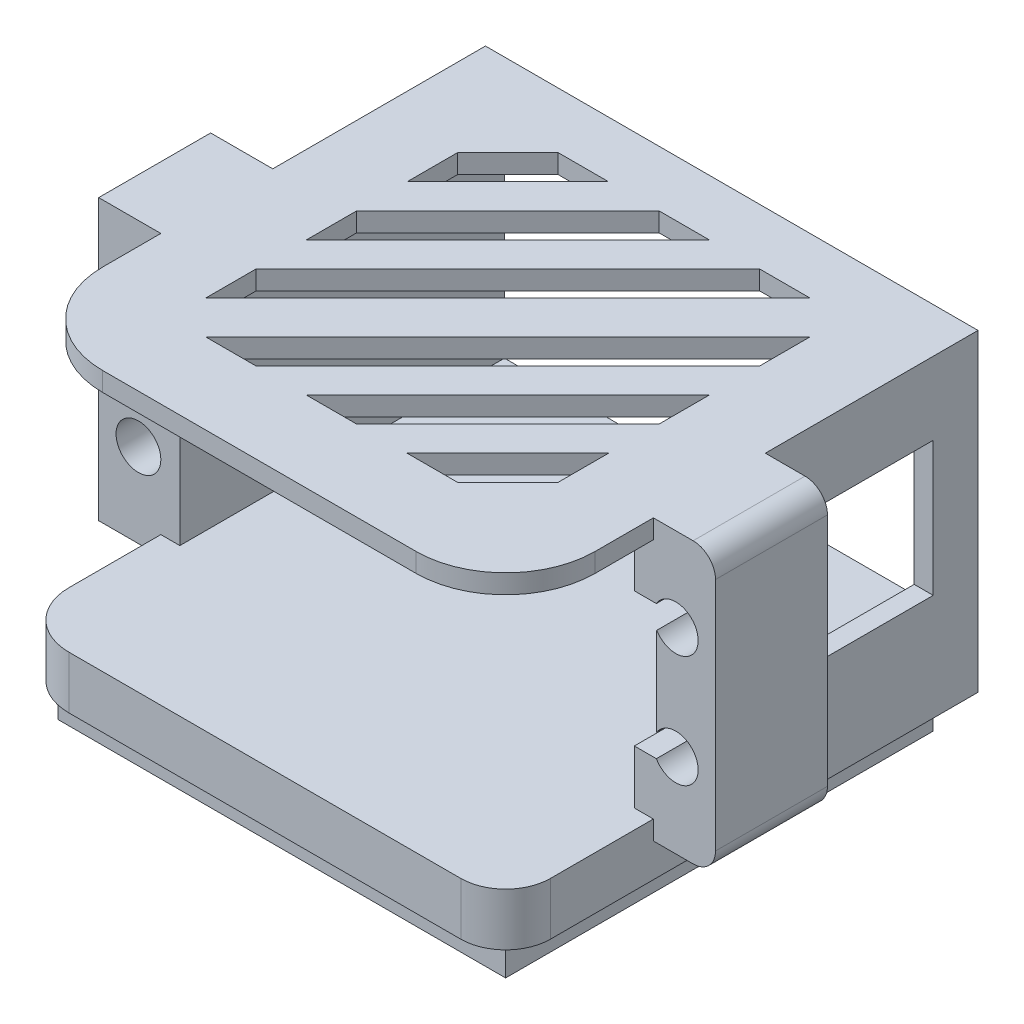
SolidWorks part; units mm, degrees
ref_plane "前视基准面" through (0, 0, 0) normal (0, 0, 1) x (1, 0, 0)
ref_plane "上视基准面" through (0, 0, 0) normal (0, 1, 0) x (1, 0, 0)
ref_plane "右视基准面" through (0, 0, 0) normal (1, 0, 0) x (0, 0, -1)
sketch "草图1" plane through (0, 0, 0) normal (0, 0, 1) x (1, 0, 0)
  line L1 (-20.3, -10.8) -> (20.3, -10.8)
  line L2 (-20.3, -10.8) -> (-20.3, 10.8)
  line L3 (-20.3, 10.8) -> (20.3, 10.8)
  line L4 (20.3, -10.8) -> (20.3, 10.8)
  line L5 (-20.3, -10.8) -> (20.3, 10.8) construction
  line L6 (-20.3, 10.8) -> (20.3, -10.8) construction
  line L7 (-22, -12.5) -> (22, -12.5)
  line L8 (-22, -12.5) -> (-22, 12.5)
  line L9 (-22, 12.5) -> (22, 12.5)
  line L10 (22, -12.5) -> (22, 12.5)
  line L11 (-22, -12.5) -> (22, 12.5) construction
  line L12 (-22, 12.5) -> (22, -12.5) construction
  point P0 (0, 0)
  point P6 (0, 0)
  dimension "D1" = 21.6
  dimension "D2" = 40.6
  dimension "D3" = 44
  dimension "D4" = 25
extrude "凸台-拉伸1" add sketch "草图1" against normal blind 44.2
ref_plane "基准面1" through (0, 0, -13.2) normal (0, 0, -1) x (-1, 0, 0)
sketch "草图2" plane through (0, 0, -13.2) normal (0, 0, -1) x (-1, 0, 0)
  line L0 (22, -12.5) -> (-22, -12.5) construction
  line L1 (-22, 12.5) -> (-27.55, 12.5)
  line L2 (-22, 12.5) -> (-22, -12.5)
  line L3 (-22, -12.5) -> (-27.55, -12.5)
  line L4 (-27.55, 12.5) -> (-27.55, -12.5)
  line L5 (0, 21.6198) -> (0, -41.7278) construction
  line L6 (0, 55) -> (0, -55) construction
  line L7 (27.55, 12.5) -> (27.55, -12.5)
  line L8 (22, -12.5) -> (27.55, -12.5)
  line L9 (22, 12.5) -> (22, -12.5)
  line L10 (22, 12.5) -> (27.55, 12.5)
  dimension "D1" = 55.1
extrude "凸台-拉伸2" add sketch "草图2" along normal blind 10
sketch "草图3" plane through (0, 0, 0) normal (0, 0, 1) x (1, 0, 0)
  line L0 (22, -12.5) -> (22, 12.5) construction
  line L1 (22, 10.8) -> (-22, 10.8)
  line L2 (22, 10.8) -> (22, -10.8)
  line L3 (22, -10.8) -> (-22, -10.8)
  line L4 (-22, 10.8) -> (-22, -10.8)
  line L5 (-22, 12.5) -> (-22, -12.5) construction
  line L6 (-20.3, -10.8) -> (20.3, -10.8) construction
  line L7 (20.3, 10.8) -> (-20.3, 10.8) construction
extrude "切除-拉伸1" cut sketch "草图3" against normal up to surface (13.2 mm away) up to face at (-24.775, 0, -13.2)
sketch "草图4" plane through (0, 0, -13.2) normal (0, 0, 1) x (1, 0, 0)
  line L0 (0, 18.9013) -> (0, -24.0465) construction
  line L1 (0, -55) -> (0, 55) construction
  line L2 (-35.4595, 0) -> (45.8751, 0) construction
  line L3 (55, 0) -> (-55, 0) construction
  circle A0 centre (24, 5) radius 2
  circle A1 centre (24, -5) radius 2
  circle A2 centre (-24, 5) radius 2
  circle A3 centre (-24, -5) radius 2
  dimension "D1" = 4
  dimension "D2" = 10
  dimension "D3" = 48
extrude "切除-拉伸2" cut sketch "草图4" against normal blind 10
fillet "圆角1" radius 2 2 edges at (27.55, -12.5, -18.2) (27.55, 12.5, -18.2)
sketch "草图5" plane through (0, -12.5, 0) normal (0, -1, 0) x (1, 0, 0)
  line L0 (13.75, 0) -> (-13.75, 0) construction
  line L1 (22, -44.2) -> (-22, -44.2)
  line L2 (22, -44.2) -> (22, 0)
  line L3 (22, 0) -> (-22, 0)
  line L4 (-22, -44.2) -> (-22, 0)
  line L5 (-22, -13.2) -> (-22, 0) construction
extrude "凸台-拉伸3" add sketch "草图5" along normal blind 6
sketch "草图9" plane through (0, -18.5, 0) normal (0, -1, 0) x (1, 0, 0)
  line L1 (-46.2786, -52.2) -> (33.7214, -52.2)
  line L2 (33.7214, -52.2) -> (58.4427, 23.8845)
  line L3 (58.4427, 23.8845) -> (-6.2786, 70.9073)
  line L4 (-6.2786, 70.9073) -> (-71, 23.8845)
  line L5 (-71, 23.8845) -> (-46.2786, -52.2)
  line L6 (-22, -44.2) -> (22, -44.2) construction
  line L7 (-22, 0) -> (-22, -44.2) construction
  circle A0 centre (-6.2786, 2.8553) radius 55.0553 construction
  circle A1 centre (-6.2786, 2.8553) radius 1
  dimension "D2" = 2
  dimension "D1" = 80
  dimension "D3" = 8
  dimension "D4" = 49
extrude "凸台-拉伸4" add sketch "草图9" along normal blind 2
sketch "草图10" plane through (0, -18.5, 0) normal (0, 1, 0) x (1, 0, 0)
  line L20 (-46.2786, 52.2) -> (33.7214, 52.2) construction
  line L21 (-64.5344, -21.7837) -> (-6.2786, -64.109)
  line L22 (-6.2786, -64.109) -> (51.9771, -21.7837)
  line L23 (51.9771, -21.7837) -> (29.7254, 46.7)
  line L24 (29.7254, 46.7) -> (-42.2827, 46.7)
  line L25 (-42.2827, 46.7) -> (-64.5344, -21.7837)
  line L26 (-62.1832, -21.0198) -> (-6.2786, -61.6368)
  line L27 (-6.2786, -61.6368) -> (49.6259, -21.0198)
  line L28 (49.6259, -21.0198) -> (28.2723, 44.7)
  line L29 (28.2723, 44.7) -> (-40.8296, 44.7)
  line L30 (-40.8296, 44.7) -> (-62.1832, -21.0198)
  circle A0 centre (-6.2786, -2.8553) radius 49.5553 construction
  circle A1 centre (-6.2786, -2.8553) radius 47.5553 construction
  dimension "D1" = 2
  dimension "D2" = 5.5
extrude "凸台-拉伸5" add sketch "草图10" along normal blind 1.5
sketch "草图11" plane through (0, 0, 0) normal (0, 0, 1) x (1, 0, 0)
  line L0 (-24, 5) -> (-24, -5) construction
  line L1 (24.31, 0) -> (-24.31, 0) construction
  line L2 (-0.1, -14.665) -> (-0.1, -18.5)
  line L3 (-64.5344, -18.5) -> (-6.2786, -18.5) construction
  line L4 (-0.1, -18.5) -> (19.9, -18.5)
  line L5 (19.9, -18.5) -> (19.9, -14.665)
  line L6 (58.4427, -18.5) -> (-6.2786, -18.5) construction
  line L7 (9.9, 0) -> (9.9, -27.5805) construction
  arc A0 (-0.1, -14.665) -> (19.9, -14.665) centre (9.9, 0) ccw
  dimension "D1" = 35.5
  dimension "D2" = 33.9
  dimension "D3" = 20
sketch "草图12" plane through (0, -20.5, 0) normal (0, -1, 0) x (1, 0, 0)
  circle A0 centre (-6.2786, 2.8553) radius 35.05
  circle A1 centre (-6.2786, 2.8553) radius 32.9
  dimension "D1" = 65.8
  dimension "D2" = 70.1
extrude "切除-拉伸6" cut sketch "草图12" against normal blind 1
sketch "草图13" plane through (0, -20.5, 0) normal (0, -1, 0) x (1, 0, 0)
  line L0 (-6.2786, 70.9073) -> (-6.2786, -52.2) construction
  line L1 (-46.2786, -52.2) -> (33.7214, -52.2) construction
  circle A1 centre (-6.2786, 65.8553) radius 1.5
  circle A2 centre (53.6379, 22.3233) radius 1.5
  circle A3 centre (30.7518, -48.1128) radius 1.5
  circle A4 centre (-43.3091, -48.1128) radius 1.5
  circle A5 centre (-66.1952, 22.3233) radius 1.5
  circle A6 centre (-6.2786, 2.8553) radius 1 construction
  point P20 (-6.2786, 2.8553)
  dimension "D1" = 3
  dimension "D2" = 63
  dimension "D3" = 5
extrude "切除-拉伸7" cut sketch "草图13" against normal blind 30
sketch "草图14" plane through (0, 0, -13.2) normal (0, 0, 1) x (1, 0, 0)
  line L0 (20.3, 10.8) -> (20.3, -10.8) construction
  line L1 (20.3, 6) -> (22.3, 6)
  line L2 (20.3, 6) -> (20.3, -6)
  line L3 (20.3, -6) -> (22.3, -6)
  line L4 (22.3, 6) -> (22.3, -6)
  line L5 (6.857, 0) -> (36.2359, 0) construction
  line L6 (24.31, 0) -> (-24.31, 0) construction
  dimension "D1" = 12
  dimension "D2" = 2
extrude "切除-拉伸8" cut sketch "草图14" against normal blind 25
fillet "圆角2" radius 8 2 edges at (-22, 11.65, 0) (22, 11.65, 0)
sketch "草图16" plane through (0, -18.5, 0) normal (0, 1, 0) x (1, 0, 0)
  line L0 (-6.2786, -2.8553) -> (-6.2786, -65.8553) construction
  line L2 (-14.6349, -12.8139) -> (-6.2786, -2.8553) construction
  line L3 (-10.3929, -6.9753) -> (-17.5702, -6.2209) construction
  line L4 (-17.5702, -6.2209) -> (-21.8122, -12.0595) construction
  line L5 (-21.8122, -12.0595) -> (-18.8769, -18.6524) construction
  line L6 (-18.8769, -18.6524) -> (-11.6995, -19.4068) construction
  line L7 (-11.6995, -19.4068) -> (-7.4575, -13.5682) construction
  line L8 (-7.4575, -13.5682) -> (-10.3929, -6.9753) construction
  circle A0 centre (-14.6349, -12.8139) radius 6.25 construction
  circle A1 centre (-14.6349, -12.8139) radius 7.2169
  dimension "D4" = 14.4338
  dimension "D1" = 40
  dimension "D2" = 13
  dimension "D3" = 12.5
extrude "切除-拉伸10" cut sketch "草图16" against normal blind 10
fillet "圆角3" radius 4 2 edges at (22, -14.65, 0) (-22, -14.65, 0)
sketch "草图17" plane through (0, 12.5, 0) normal (0, 1, 0) x (1, 0, 0)
  line L0 (-22, 4) -> (-22, 44.2) construction
  line L1 (-22, 44.2) -> (22, 44.2)
  line L2 (-22, 44.2) -> (-22, 42.2)
  line L3 (-22, 42.2) -> (22, 42.2)
  line L4 (22, 44.2) -> (22, 42.2)
  line L5 (-22, 44.2) -> (-22, 23.2) construction
  line L6 (22, 44.2) -> (22, 4) construction
  line L7 (-22, 44.2) -> (22, 44.2) construction
  dimension "D1" = 2
extrude "切除-拉伸11" cut sketch "草图17" against normal up to surface (31 mm away) up to face at (-14.6349, -18.5, 20.0307)
ref_plane "基准面2" through (0, -15.5, 0) normal (0, 1, 0) x (1, 0, 0)
sketch "草图21" plane through (0, -15.5, 0) normal (0, 1, 0) x (1, 0, 0)
  line L1 (111.3264, -97.0862) -> (-116.3675, -97.0862)
  line L2 (111.3264, -97.0862) -> (111.3264, 94.8272)
  line L3 (111.3264, 94.8272) -> (-116.3675, 94.8272)
  line L4 (-116.3675, -97.0862) -> (-116.3675, 94.8272)
extrude "切除-拉伸15" cut sketch "草图21" against normal blind 16
sketch "草图25" plane through (0, -10.8, 0) normal (0, 1, 0) x (1, 0, 0)
  line L0 (-22, 13.2) -> (-22, 4) construction
  line L1 (-18, 0) -> (18, 0) construction
  line L2 (-22, 5) -> (-22, 0)
  line L3 (-22, 0) -> (-17, 0)
  arc A0 (-22, 5) -> (-17, 0) centre (-17, 5) ccw
  dimension "D1" = 10
extrude "切除-拉伸17" cut sketch "草图25" against normal blind 10
sketch "草图31" plane through (0, -15.5, 0) normal (0, -1, 0) x (1, 0, 0)
  line L0 (0, -22.0443) -> (0, 22.0443) construction
  line L1 (-20, -40.2) -> (20, -40.2)
  line L2 (-20, -40.2) -> (-20, -2)
  line L3 (-20, -2) -> (20, -2)
  line L4 (20, -40.2) -> (20, -2)
  line L5 (-20, -40.2) -> (20, -2) construction
  line L6 (-20, -2) -> (20, -40.2) construction
  line L7 (19.9, 0) -> (-0.1, 0) construction
  line L8 (22, -42.2) -> (-22, -42.2) construction
  point P0 (0, -21.1)
  dimension "D1" = 40
  dimension "D2" = 2
  dimension "D3" = 2
extrude "凸台-拉伸10" add sketch "草图31" along normal blind 3
sketch "草图32" plane through (0, 12.5, 0) normal (0, 1, 0) x (1, 0, 0)
  line L0 (0, -22.0443) -> (0, 22.0443) construction
  line L1 (-15, 7.2) -> (15, 7.2) construction
  line L2 (-15, 7.2) -> (-15, 37.2) construction
  line L3 (-15, 37.2) -> (15, 37.2) construction
  line L4 (15, 7.2) -> (15, 37.2) construction
  line L5 (-15, 7.2) -> (15, 37.2) construction
  line L6 (-15, 37.2) -> (15, 7.2) construction
  line L7 (-22, 42.2) -> (22, 42.2) construction
  line L8 (-10.5, 37.2) -> (-15, 32.7)
  line L9 (-15, 32.7) -> (-15, 28.2)
  line L10 (-15, 28.2) -> (-6, 37.2)
  line L11 (-6, 37.2) -> (-10.5, 37.2)
  line L12 (-1.5, 37.2) -> (-15, 23.7)
  line L13 (-15, 23.7) -> (-15, 19.2)
  line L14 (-15, 19.2) -> (3, 37.2)
  line L15 (3, 37.2) -> (-1.5, 37.2)
  line L16 (7.5, 37.2) -> (-15, 14.7)
  line L17 (-15, 14.7) -> (-15, 10.2)
  line L18 (-15, 10.2) -> (12, 37.2)
  line L19 (12, 37.2) -> (7.5, 37.2)
  line L20 (-7.5, 7.2) -> (-12, 7.2)
  line L21 (1.5, 7.2) -> (-3, 7.2)
  line L22 (15, 34.2) -> (15, 29.7)
  line L23 (-12, 7.2) -> (15, 34.2)
  line L24 (15, 29.7) -> (-7.5, 7.2)
  line L25 (15, 25.2) -> (15, 20.7)
  line L26 (-3, 7.2) -> (15, 25.2)
  line L27 (15, 20.7) -> (1.5, 7.2)
  line L28 (15, 16.2) -> (15, 11.7)
  line L29 (6, 7.2) -> (15, 16.2)
  line L30 (10.5, 7.2) -> (6, 7.2)
  line L31 (15, 11.7) -> (10.5, 7.2)
  point P0 (0, 22.2)
  dimension "D1" = 30
  dimension "D2" = 30
  dimension "D3" = 20
  dimension "D4" = 45
  dimension "D5" = 4.5
  dimension "D6" = 4.5
  dimension "D7" = 4.5
  dimension "D8" = 4.5
  dimension "D9" = 4.5
  dimension "D10" = 4.5
  dimension "D11" = 4.5
extrude "切除-拉伸18" cut sketch "草图32" against normal blind 2
